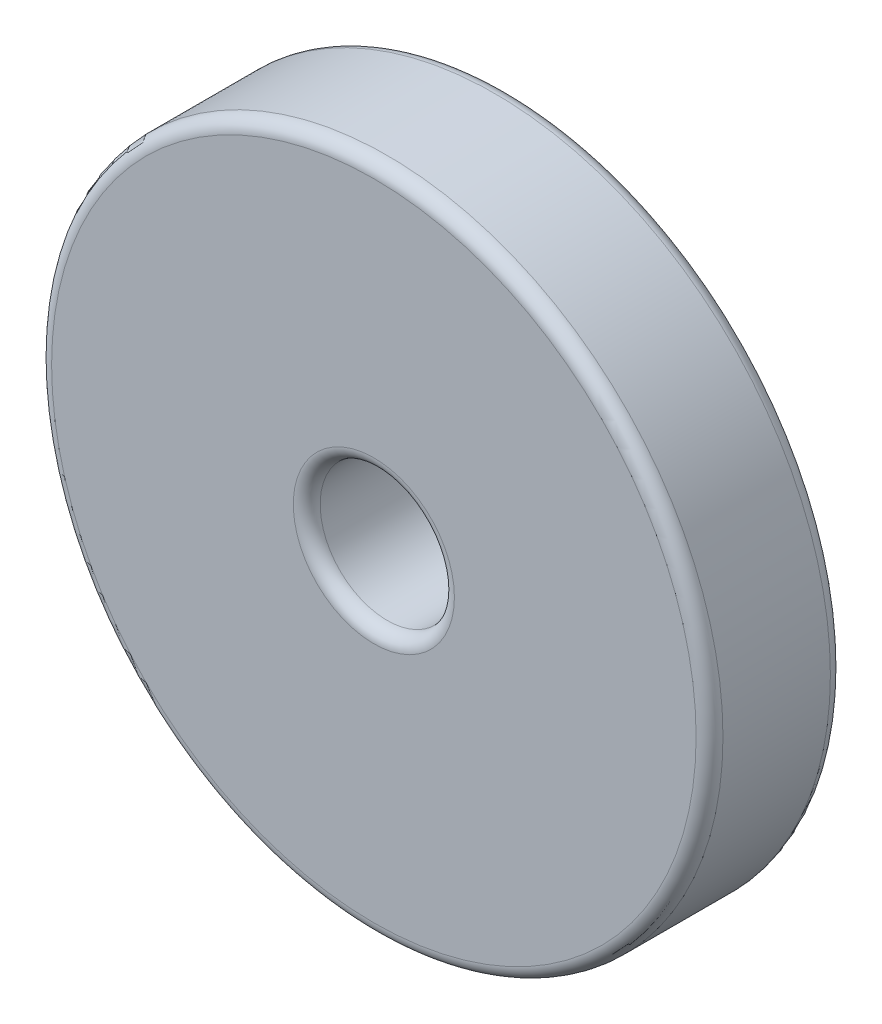
SolidWorks part; units mm, degrees
ref_plane "Front Plane" through (0, 0, 0) normal (0, 0, 1) x (1, 0, 0)
ref_plane "Top Plane" through (0, 0, 0) normal (0, 1, 0) x (1, 0, 0)
ref_plane "Right Plane" through (0, 0, 0) normal (1, 0, 0) x (0, 0, -1)
sketch "Sketch1" plane through (0, 0, 0) normal (0, 0, 1) x (1, 0, 0)
  circle A0 centre (0, 0) radius 25
  circle A1 centre (0, 0) radius 5
  dimension "D1" = 50
  dimension "D2" = 10
extrude "Boss-Extrude1" add sketch "Sketch1" along normal blind 10
fillet "Fillet1" radius 1 3 edges at (5, 0, 10) (25, 0, 0) (5, 0, 0)
fillet "Fillet2" radius 1 1 edges at (25, 0, 10)
